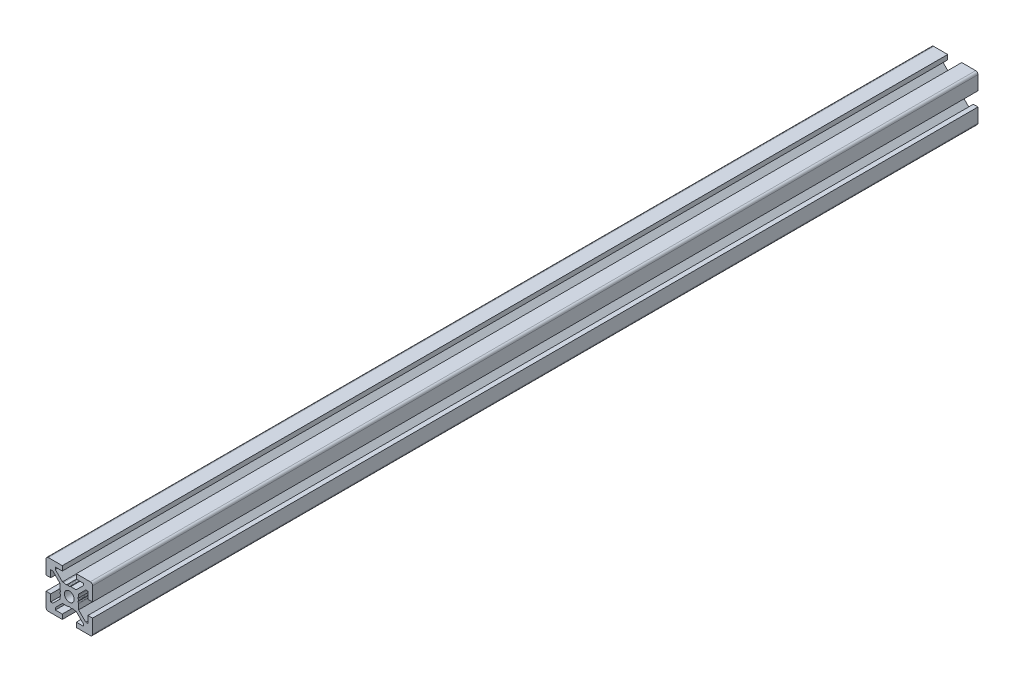
SolidWorks part; units mm, degrees
ref_plane "Front Plane" through (0, 0, 0) normal (0, 0, 1) x (1, 0, 0)
ref_plane "Top Plane" through (0, 0, 0) normal (0, 1, 0) x (1, 0, 0)
ref_plane "Right Plane" through (0, 0, 0) normal (1, 0, 0) x (0, 0, -1)
ref_plane "Plane1" through (0, 0, -2000) normal (0, 0, -1) x (-1, 0, 0)
sketch "Sketch1" plane through (0, 0, -2000) normal (0, 0, -1) x (-1, 0, 0)
  line L0 (10, -3) -> (8, -3)
  line L1 (8, -3) -> (8, -6)
  line L2 (8, -6) -> (7.0607, -6)
  line L3 (7.0607, -6) -> (4, -2.9393)
  line L4 (4, -2.9393) -> (4, -2.5)
  line L5 (4, -2.5) -> (3.751, -1.2189)
  line L6 (3.751, -1.2189) -> (3.933, -0.9036)
  line L7 (3.933, -0.4036) -> (3.7, 0)
  line L8 (3.7, 0) -> (3.933, 0.4036)
  line L9 (4, 0.6536) -> (4, 2.9393)
  line L10 (4, 2.9393) -> (7.0607, 6)
  line L11 (7.0607, 6) -> (8, 6)
  line L12 (8, 6) -> (8, 3)
  line L13 (8, 3) -> (10, 3)
  line L14 (10, 3) -> (10, 9)
  line L15 (9, 10) -> (3, 10)
  line L16 (3, 10) -> (3, 8)
  line L17 (3, 8) -> (6, 8)
  line L18 (6, 8) -> (6, 7.0607)
  line L19 (6, 7.0607) -> (2.9393, 4)
  line L20 (2.9393, 4) -> (2.5, 4)
  line L21 (2.5, 4) -> (1.2189, 3.751)
  line L22 (1.2189, 3.751) -> (0.9036, 3.933)
  line L23 (0.4036, 3.933) -> (0, 3.7)
  line L24 (0, 3.7) -> (-0.4036, 3.933)
  line L25 (-0.6536, 4) -> (-2.9393, 4)
  line L26 (-2.9393, 4) -> (-6, 7.0607)
  line L27 (-6, 7.0607) -> (-6, 8)
  line L28 (-6, 8) -> (-3, 8)
  line L29 (-3, 8) -> (-3, 10)
  line L30 (-3, 10) -> (-9, 10)
  line L31 (-10, 9) -> (-10, 3)
  line L32 (-10, 3) -> (-8, 3)
  line L33 (-8, 3) -> (-8, 6)
  line L34 (-8, 6) -> (-7.0607, 6)
  line L35 (-7.0607, 6) -> (-4, 2.9393)
  line L36 (-4, 2.9393) -> (-4, 2.5)
  line L37 (-4, 2.5) -> (-3.751, 1.2189)
  line L38 (-3.751, 1.2189) -> (-3.933, 0.9036)
  line L39 (-3.933, 0.4036) -> (-3.7, 0)
  line L40 (-3.7, 0) -> (-3.933, -0.4036)
  line L41 (-4, -0.6536) -> (-4, -2.9393)
  line L42 (-4, -2.9393) -> (-7.0607, -6)
  line L43 (-7.0607, -6) -> (-8, -6)
  line L44 (-8, -6) -> (-8, -3)
  line L45 (-8, -3) -> (-10, -3)
  line L46 (-10, -3) -> (-10, -9)
  line L47 (-9, -10) -> (-3, -10)
  line L48 (-3, -10) -> (-3, -8)
  line L49 (-3, -8) -> (-6, -8)
  line L50 (-6, -8) -> (-6, -7.0607)
  line L51 (-6, -7.0607) -> (-2.9393, -4)
  line L52 (-2.9393, -4) -> (-2.5, -4)
  line L53 (-2.5, -4) -> (-1.2189, -3.751)
  line L54 (-1.2189, -3.751) -> (-0.9036, -3.933)
  line L55 (-0.4036, -3.933) -> (0, -3.7)
  line L56 (0, -3.7) -> (0.4036, -3.933)
  line L57 (0.6536, -4) -> (2.9393, -4)
  line L58 (2.9393, -4) -> (6, -7.0607)
  line L59 (6, -7.0607) -> (6, -8)
  line L60 (6, -8) -> (3, -8)
  line L61 (3, -8) -> (3, -10)
  line L62 (3, -10) -> (9, -10)
  line L63 (10, -9) -> (10, -3)
  circle A0 centre (0, 0) radius 2.1
  arc A1 (3.933, -0.9036) -> (3.933, -0.4036) centre (3.5, -0.6536) ccw
  arc A2 (3.933, 0.4036) -> (4, 0.6536) centre (3.5, 0.6536) ccw
  arc A3 (10, 9) -> (9, 10) centre (9, 9) ccw
  arc A4 (0.9036, 3.933) -> (0.4036, 3.933) centre (0.6536, 3.5) ccw
  arc A5 (-0.4036, 3.933) -> (-0.6536, 4) centre (-0.6536, 3.5) ccw
  arc A6 (-9, 10) -> (-10, 9) centre (-9, 9) ccw
  arc A7 (-3.933, 0.9036) -> (-3.933, 0.4036) centre (-3.5, 0.6536) ccw
  arc A8 (-3.933, -0.4036) -> (-4, -0.6536) centre (-3.5, -0.6536) ccw
  arc A9 (-10, -9) -> (-9, -10) centre (-9, -9) ccw
  arc A10 (-0.9036, -3.933) -> (-0.4036, -3.933) centre (-0.6536, -3.5) ccw
  arc A11 (0.4036, -3.933) -> (0.6536, -4) centre (0.6536, -3.5) ccw
  arc A12 (9, -10) -> (10, -9) centre (9, -9) ccw
extrude "Boss-Extrude1" add sketch "Sketch1" against normal blind 380
